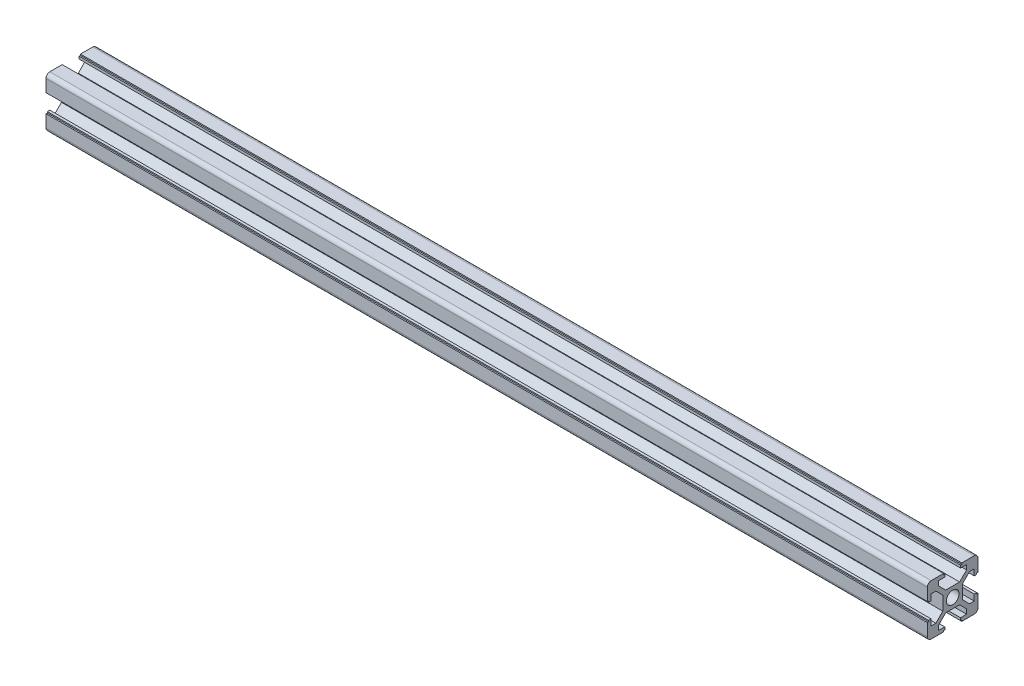
SolidWorks part; units mm, degrees
ref_plane "前视基准面" through (0, 0, 0) normal (0, 0, 1) x (1, 0, 0)
ref_plane "上视基准面" through (0, 0, 0) normal (0, 1, 0) x (1, 0, 0)
ref_plane "右视基准面" through (0, 0, 0) normal (1, 0, 0) x (0, 0, -1)
sketch "草图1" plane through (0, 0, 0) normal (0, 1, 0) x (1, 0, 0)
  line L0 (0, 0) -> (348, 0)
  dimension "D1" = 348
other "铝型材 20 X 20 X R1.5(1)"
ref_plane "基准面1" through (0, 0, 0) normal (1, 0, 0) x (0, 0, -1)
sketch "Sketch1" plane through (0, 0, 0) normal (1, 0, 0) x (0, 0, -1)
  line L0 (-3.6, 10) -> (-3.6, 9.5)
  line L1 (-3.6, 9.5) -> (-3.1, 9.5)
  line L2 (-3.1, 9.5) -> (-3.1, 8.5)
  line L3 (-3.1, 8.5) -> (-5.5, 8.5)
  line L4 (-8.5, -10) -> (-3.6, -10)
  line L5 (-10, -8.5) -> (-10, -3.6)
  line L6 (8.5, 10) -> (3.6, 10)
  line L7 (10, 8.5) -> (10, 3.6)
  line L8 (0, 14.8756) -> (0, 0) construction
  line L9 (0, 0) -> (14.1675, 0) construction
  line L10 (-5.5, 8.5) -> (-5.5, 6.65)
  line L11 (-5.5, 6.65) -> (-2.75, 3.9)
  line L12 (-2.75, 3.9) -> (2.75, 3.9)
  line L13 (5.5, 6.65) -> (2.75, 3.9)
  line L14 (5.5, 8.5) -> (5.5, 6.65)
  line L15 (3.1, 8.5) -> (5.5, 8.5)
  line L16 (3.1, 9.5) -> (3.1, 8.5)
  line L17 (3.6, 9.5) -> (3.1, 9.5)
  line L18 (3.6, 10) -> (3.6, 9.5)
  line L19 (-3.6, 10) -> (-8.5, 10)
  line L20 (10, 3.6) -> (9.5, 3.6)
  line L21 (9.5, 3.6) -> (9.5, 3.1)
  line L22 (9.5, 3.1) -> (8.5, 3.1)
  line L23 (8.5, 3.1) -> (8.5, 5.5)
  line L24 (8.5, 5.5) -> (6.65, 5.5)
  line L25 (6.65, 5.5) -> (3.9, 2.75)
  line L26 (3.9, 2.75) -> (3.9, -2.75)
  line L27 (6.65, -5.5) -> (3.9, -2.75)
  line L28 (8.5, -5.5) -> (6.65, -5.5)
  line L29 (8.5, -3.1) -> (8.5, -5.5)
  line L30 (9.5, -3.1) -> (8.5, -3.1)
  line L31 (9.5, -3.6) -> (9.5, -3.1)
  line L32 (10, -3.6) -> (9.5, -3.6)
  line L33 (3.6, -10) -> (3.6, -9.5)
  line L34 (3.6, -9.5) -> (3.1, -9.5)
  line L35 (3.1, -9.5) -> (3.1, -8.5)
  line L36 (3.1, -8.5) -> (5.5, -8.5)
  line L37 (5.5, -8.5) -> (5.5, -6.65)
  line L38 (5.5, -6.65) -> (2.75, -3.9)
  line L39 (2.75, -3.9) -> (-2.75, -3.9)
  line L40 (-5.5, -6.65) -> (-2.75, -3.9)
  line L41 (-5.5, -8.5) -> (-5.5, -6.65)
  line L42 (-3.1, -8.5) -> (-5.5, -8.5)
  line L43 (-3.1, -9.5) -> (-3.1, -8.5)
  line L44 (-3.6, -9.5) -> (-3.1, -9.5)
  line L45 (-3.6, -10) -> (-3.6, -9.5)
  line L46 (-10, -3.6) -> (-9.5, -3.6)
  line L47 (-9.5, -3.6) -> (-9.5, -3.1)
  line L48 (-9.5, -3.1) -> (-8.5, -3.1)
  line L49 (-8.5, -3.1) -> (-8.5, -5.5)
  line L50 (-8.5, -5.5) -> (-6.65, -5.5)
  line L51 (-6.65, -5.5) -> (-3.9, -2.75)
  line L52 (-3.9, -2.75) -> (-3.9, 2.75)
  line L53 (-6.65, 5.5) -> (-3.9, 2.75)
  line L54 (-8.5, 5.5) -> (-6.65, 5.5)
  line L55 (-8.5, 3.1) -> (-8.5, 5.5)
  line L56 (-9.5, 3.1) -> (-8.5, 3.1)
  line L57 (-9.5, 3.6) -> (-9.5, 3.1)
  line L58 (-10, 3.6) -> (-9.5, 3.6)
  line L59 (3.6, -10) -> (8.5, -10)
  line L60 (-10, 3.6) -> (-10, 8.5)
  line L61 (10, -3.6) -> (10, -8.5)
  circle A0 centre (0, 0) radius 2.5
  arc A1 (-10, 8.5) -> (-8.5, 10) centre (-8.5, 8.5) cw
  arc A2 (10, 8.5) -> (8.5, 10) centre (8.5, 8.5) ccw
  arc A3 (-8.5, -10) -> (-10, -8.5) centre (-8.5, -8.5) cw
  arc A4 (8.5, -10) -> (10, -8.5) centre (8.5, -8.5) ccw
  point P0 (-10, 0)
  point P1 (10, 0)
  point P2 (0, 10)
  point P3 (0, -10)
  point P4 (0, 0)
  point P5 (-10, -10)
  point P6 (10, -10)
  point P7 (10, 10)
  point P8 (-10, 10)
  point P13 (0, 0)
  point P36 (-10, 10)
  point P39 (10, 10)
  dimension "D1" = 11
  dimension "D2" = 20
  dimension "D3" = 6.2
  dimension "D4" = 7.2
  dimension "D5" = 6.1
  dimension "D6" = 5
  dimension "D7" = 1.5
  dimension "D8" = 45
  dimension "D9" = 0.5
  dimension "D10" = 1
  dimension "D11" = 5.5
